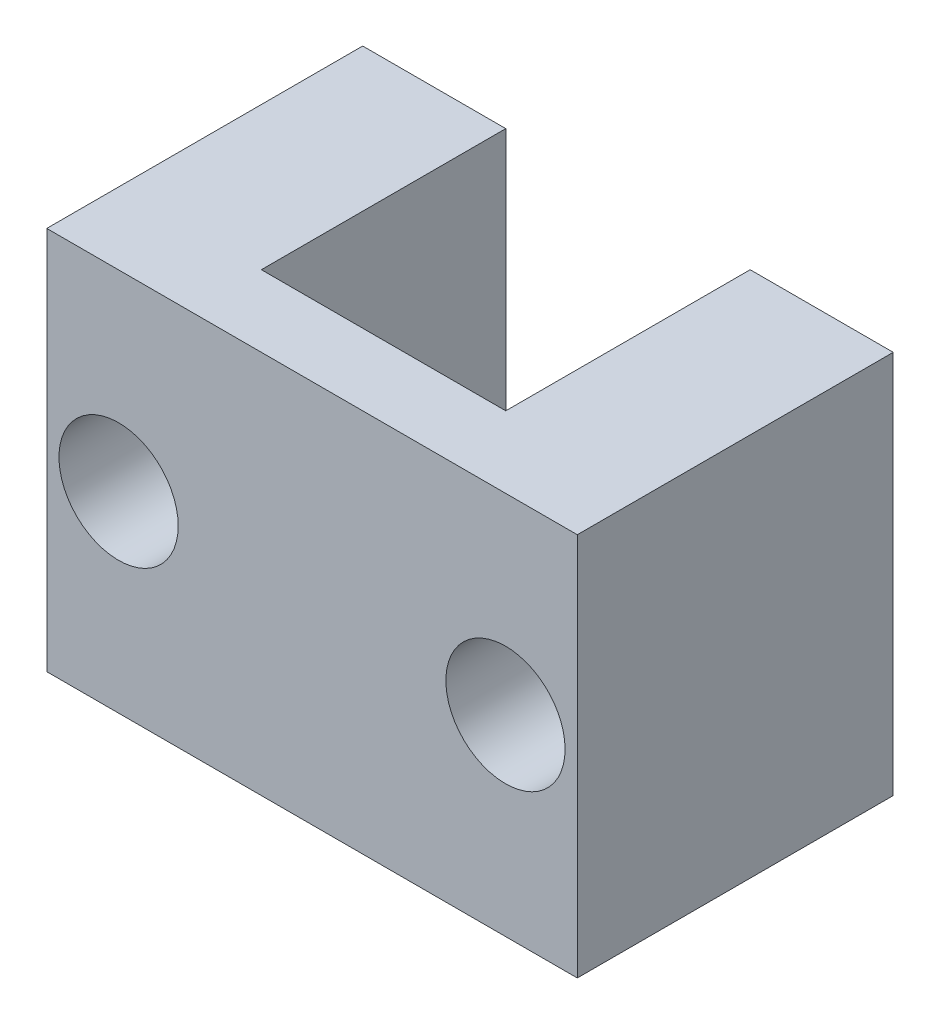
SolidWorks part; units mm, degrees
material "PA12CF"
ref_plane "Płaszczyzna przednia" through (0, 0, 0) normal (0, 0, 1) x (1, 0, 0)
ref_plane "Płaszczyzna górna" through (0, 0, 0) normal (0, 1, 0) x (1, 0, 0)
ref_plane "Płaszczyzna prawa" through (0, 0, 0) normal (1, 0, 0) x (0, 0, -1)
sketch "Sketch1" plane through (0, 0, 0) normal (0, 0, 1) x (1, 0, 0)
  line L1 (0, 0) -> (44.5, 0)
  line L2 (0, 0) -> (0, 32.2)
  line L3 (0, 32.2) -> (44.5, 32.2)
  line L4 (44.5, 0) -> (44.5, 32.2)
  dimension "D1" = 44.5
  dimension "D2" = 32.2
extrude "Boss-Extrude1" add sketch "Sketch1" along normal blind 6
sketch "Sketch2" plane through (0, 0, 0) normal (0, 0, -1) x (-1, 0, 0)
  line L0 (0, 0) -> (-44.5, 0) construction
  line L1 (-44.5, 32.2) -> (-32.5, 32.2)
  line L2 (-44.5, 32.2) -> (-44.5, 0)
  line L3 (-44.5, 0) -> (-32.5, 0)
  line L4 (-32.5, 32.2) -> (-32.5, 0)
  line L5 (-44.5, 32.2) -> (0, 32.2) construction
  line L6 (0, 0) -> (-12, 0)
  line L7 (0, 0) -> (0, 32.2)
  line L8 (0, 32.2) -> (-12, 32.2)
  line L9 (-12, 0) -> (-12, 32.2)
  dimension "D1" = 12
extrude "Boss-Extrude2" add sketch "Sketch2" along normal blind 20.5
hole_wizard "CBORE for M5 Hex Socket Head Cap Screw1" positions "Sketch3" profile "Sketch4" counterbore size "M5" standard "DIN" end condition through all
sketch "Sketch3" plane through (0, 0, 6) normal (0, 0, 1) x (1, 0, 0)
  point P0 (6.025, 16.1)
  point P2 (38.475, 16.1)
  point P5 (0, 0)
  point P6 (0, 0)
  point P7 (6.025, 16.1)
  point P9 (38.475, 16.1)
sketch "Sketch4" plane through (6.025, 16.1, 6) normal (1, 0, 0) x (0, -1, 0)
  line L0 (0, 0) -> (0, 26.5)
  line L1 (0, 26.5) -> (2.9, 26.5)
  line L3 (2.9, 26.5) -> (2.9, 7.4)
  line L4 (2.9, 7.4) -> (5, 7.4)
  line L5 (5, 7.4) -> (5, 0)
  line L7 (5, 0) -> (0, 0)
  line L11 (0, -6.35) -> (0, 107.95) construction
  dimension "Thru Hole Dia." = 5.8
  dimension "Thru Hole Depth" = 26.5
  dimension "C'Bore Dia." = 10
  dimension "C'Bore Depth" = 7.4
sketch "Sketch6" plane through (0, 0, 0) normal (0, 0, -1) x (-1, 0, 0)
  line L0 (-31.5, 1) -> (-13, 1)
  line L1 (-13, 1) -> (-13, 31.2)
  line L2 (-13, 31.2) -> (-31.5, 31.2)
  line L3 (-31.5, 31.2) -> (-31.5, 1)
  line L4 (-32.5, 0) -> (-12, 0)
  line L5 (-12, 0) -> (-12, 32.2)
  line L6 (-12, 32.2) -> (-32.5, 32.2)
  line L7 (-32.5, 32.2) -> (-32.5, 0)
  line L8 (-32.5, 0) -> (-12, 0)
  line L9 (-12, 0) -> (-12, 32.2)
  line L10 (-12, 32.2) -> (-32.5, 32.2)
  line L11 (-32.5, 32.2) -> (-32.5, 0)
  dimension "D1" = 0
  dimension "D2" = 1
extrude "Cut-Extrude1" cut sketch "Sketch6" against normal blind 1 contours L2 L3 L0 L1
